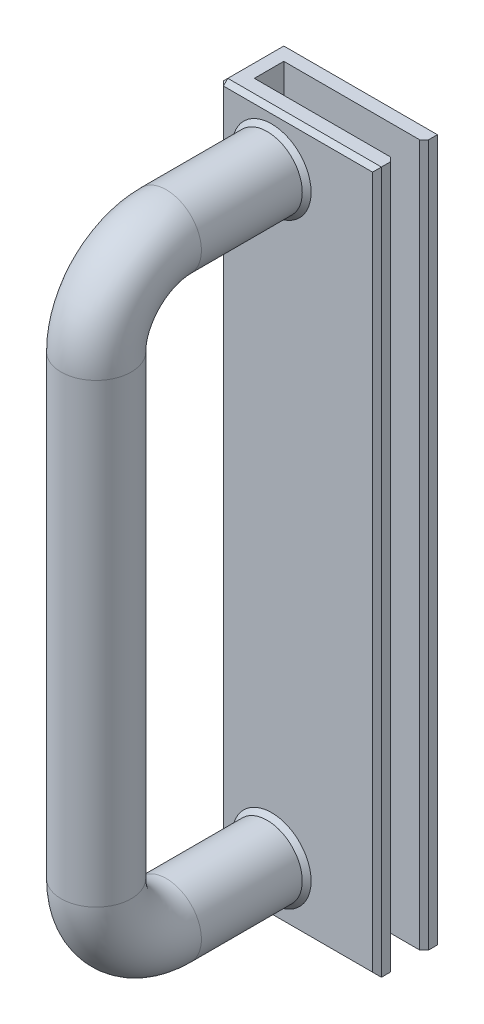
SolidWorks part; units mm, degrees
ref_plane "Front Plane" through (0, 0, 0) normal (0, 0, 1) x (1, 0, 0)
ref_plane "Top Plane" through (0, 0, 0) normal (0, 1, 0) x (1, 0, 0)
ref_plane "Right Plane" through (0, 0, 0) normal (1, 0, 0) x (0, 0, -1)
sketch "Sketch1" plane through (0, 0, 0) normal (0, 1, 0) x (1, 0, 0)
  line L0 (-12.7, 2.667) -> (12.7, 2.667)
  line L1 (-12.7, -2.667) -> (12.7, -2.667) construction
  line L2 (-12.7, -2.667) -> (-12.7, 2.667) construction
  line L3 (-12.7, 2.667) -> (12.7, 2.667) construction
  line L4 (12.7, -2.667) -> (12.7, 2.667) construction
  line L5 (-12.7, -2.667) -> (12.7, 2.667) construction
  line L6 (-12.7, 2.667) -> (12.7, -2.667) construction
  line L7 (12.7, 2.667) -> (12.7, -2.667)
  line L8 (12.7, -2.667) -> (-12.7, -2.667)
  line L9 (-12.7, -2.667) -> (-12.7, -5.867)
  line L10 (-12.7, -5.867) -> (15.9, -5.867)
  line L11 (15.9, -5.867) -> (15.9, 5.867)
  line L12 (15.9, 5.867) -> (-12.7, 5.867)
  line L13 (-12.7, 5.867) -> (-12.7, 2.667)
  point P0 (0, 0)
  dimension "D1" = 5.334
  dimension "D2" = 25.4
  dimension "D3" = 3.2
  dimension "D4" = 3.2
extrude "Boss-Extrude1" add sketch "Sketch1" along normal blind 127 contours L0 L7 L8 L9 L10 L11 L12 L13
sketch "Sketch2" plane through (0, 0, 5.867) normal (0, 0, 1) x (1, 0, 0)
  line L6 (-12.7, 0) -> (15.9, 0) construction
  line L7 (15.9, 127) -> (15.9, 0) construction
  circle A4 centre (6.375, 9.525) radius 6.35
  dimension "D1" = 12.7
  dimension "D3" = 3.175
  dimension "D2" = 3.175
sketch3d "3DSketch1"
  line L0 (6.375, 9.525, 5.867) -> (6.375, 9.525, 24.917)
  line L1 (6.375, 22.225, 37.617) -> (6.375, 104.775, 37.617)
  line L2 (6.375, 117.475, 24.917) -> (6.375, 117.475, 5.867)
  line L3 (6.375, 9.525, 5.867) -> (6.375, 0, 5.867) construction
  line L4 (-12.7, 0, 5.867) -> (15.9, 0, 5.867) construction
  line L5 (6.375, 117.475, 5.867) -> (6.375, 127, 5.867) construction
  line L6 (-12.7, 127, 5.867) -> (15.9, 127, 5.867) construction
  arc A0 (6.375, 9.525, 24.917) -> (6.375, 22.225, 37.617) centre (6.375, 22.225, 24.917) cw
  arc A1 (6.375, 104.775, 37.617) -> (6.375, 117.475, 24.917) centre (6.375, 104.775, 24.917) cw
  point P4 (-6.325, 22.225, 24.917)
  point P7 (-6.325, 104.775, 24.917)
  dimension "D1" = 12.7
  dimension "D2" = 31.75
sweep "Sweep1" add profiles "Sketch2" path "3DSketch1"
chamfer "Chamfer1" distance 0.8 angle 45 14 edges at (-12.7, 63.5, -2.667) (-12.7, 63.5, 2.667) (1.6, 0, -5.867) (15.9, 0, 0) (1.6, 0, 5.867) (15.9, 63.5, -5.867) (15.9, 63.5, 5.867) (-12.7, 63.5, -5.867) (1.6, 127, -5.867) (15.9, 127, 0) (1.6, 127, 5.867) (-12.7, 63.5, 5.867) (12.725, 9.525, 5.867) (12.725, 117.475, 5.867)
mirror "Mirror3" about plane through (0, 0, 0) normal (1, 0, 0) of bodies 102
delete or keep bodies "Body-Delete/Keep 1" type delete bodies bodies 102
equation "\"w\"= 0.4mm"
equation "\"D3@Sketch1\"=8*\"w\""
equation "\"D4@Sketch1\"=8*\"w\""
equation "\"panel\"= .220in'thickness of the polycarb"
equation "\"panel-interference\"= .01in'magnitude of the interference fit"
equation "\"slot-width\"= \"panel\" - \"panel-interference\""
equation "\"D1@Sketch1\"=\"slot-width\""
